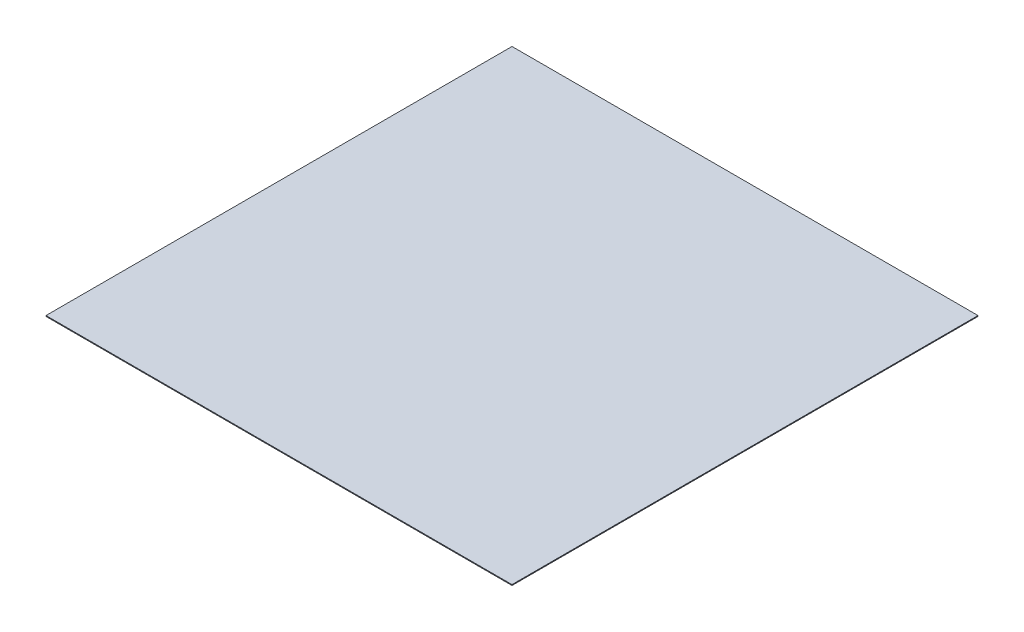
SolidWorks part; units mm, degrees
material "STYCAST 2850FT/Catalyst 23LV"
ref_plane "Front Plane" through (0, 0, 0) normal (0, 0, 1) x (1, 0, 0)
ref_plane "Top Plane" through (0, 0, 0) normal (0, 1, 0) x (1, 0, 0)
ref_plane "Right Plane" through (0, 0, 0) normal (1, 0, 0) x (0, 0, -1)
sketch "Sketch1" plane through (0, 0, 0) normal (0, 1, 0) x (1, 0, 0)
  line L1 (-69.85, -69.85) -> (69.85, -69.85)
  line L2 (-69.85, -69.85) -> (-69.85, 69.85)
  line L3 (-69.85, 69.85) -> (69.85, 69.85)
  line L4 (69.85, -69.85) -> (69.85, 69.85)
  line L5 (-69.85, -69.85) -> (69.85, 69.85) construction
  line L6 (-69.85, 69.85) -> (69.85, -69.85) construction
  point P0 (0, 0)
  dimension "D1" = 139.7
extrude "Boss-Extrude1" add sketch "Sketch1" along normal mid plane 0.25
equation "\"panel_width\"= 5.5in"
equation "\"finger_joint_width\" = 30mm"
equation "\"D1@Sketch1\"=\"panel_width\""
